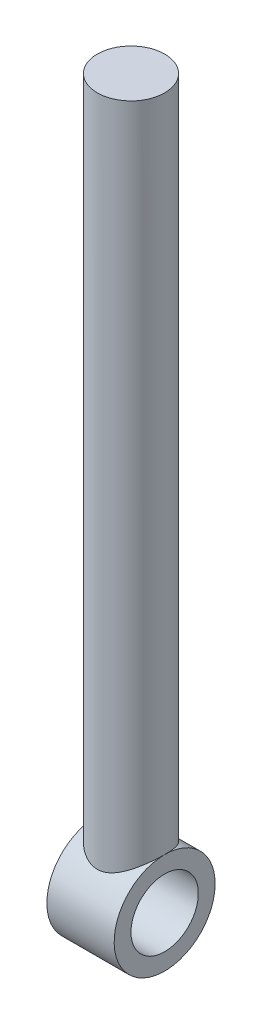
SolidWorks part; units mm, degrees
ref_plane "Front Plane" through (0, 0, 0) normal (0, 0, 1) x (1, 0, 0)
ref_plane "Top Plane" through (0, 0, 0) normal (0, 1, 0) x (1, 0, 0)
ref_plane "Right Plane" through (0, 0, 0) normal (1, 0, 0) x (0, 0, -1)
sketch "Sketch1" plane through (0, 0, 0) normal (0, 0, 1) x (1, 0, 0)
  line L0 (1.1287, -94.2511) -> (1.1287, 5.7489) construction
  line L1 (-1.3713, 5.7489) -> (3.6287, 5.7489)
  line L2 (-1.3713, 5.7489) -> (-1.3713, -94.2511)
  line L3 (-1.3713, -94.2511) -> (3.6287, -94.2511)
  line L4 (3.6287, 5.7489) -> (3.6287, -94.2511)
  dimension "D1" = 5
  dimension "D2" = 100
revolve "Revolve1" add sketch "Sketch1" angle 360 about L2
sketch "Sketch3" plane through (0, 0, 0) normal (0, 0, 1) x (1, 0, 0)
  line L0 (-6.3713, 5.7489) -> (-6.3713, -94.2511) construction
  line L1 (-6.3713, -92.2511) -> (3.6287, -92.2511)
  line L2 (-6.3713, -92.2511) -> (-6.3713, -94.7511)
  line L3 (-6.3713, -94.7511) -> (3.6287, -94.7511)
  line L4 (3.6287, -92.2511) -> (3.6287, -94.7511)
  line L5 (3.6287, -94.2511) -> (3.6287, 5.7489) construction
  line L6 (-6.3713, -94.2511) -> (3.6287, -94.2511) construction
  line L7 (-6.8258, -99.7511) -> (5.0095, -99.7511) construction
  dimension "D1" = 0
  dimension "D2" = 10
  dimension "D3" = 2.5
  dimension "D4" = 2
  dimension "D5" = 5
revolve "Revolve2" add sketch "Sketch3" angle 360 about L7
